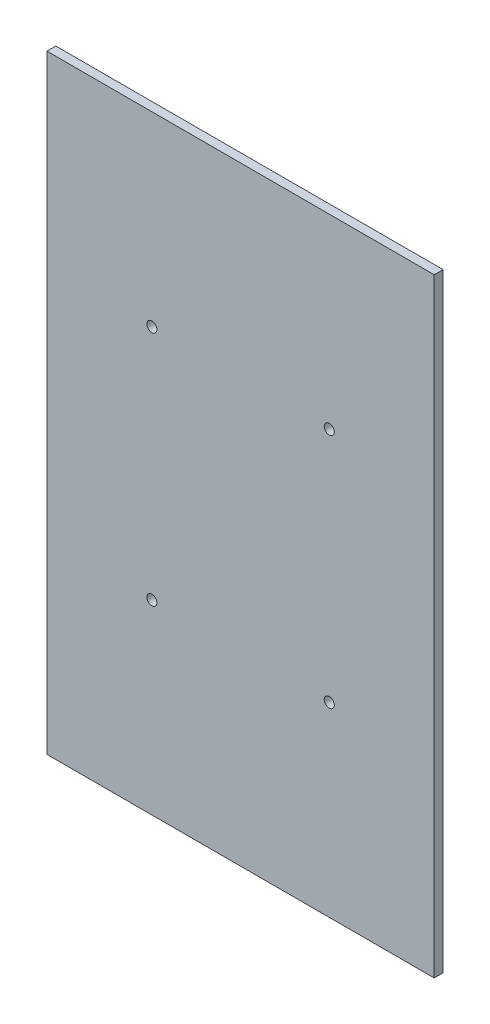
SolidWorks part; units mm, degrees
ref_plane "Front Plane" through (0, 0, 0) normal (0, 0, 1) x (1, 0, 0)
ref_plane "Top Plane" through (0, 0, 0) normal (0, 1, 0) x (1, 0, 0)
ref_plane "Right Plane" through (0, 0, 0) normal (1, 0, 0) x (0, 0, -1)
sketch "Sketch2" plane through (0, 0, 0) normal (0, 0, 1) x (1, 0, 0)
  line L1 (-65.5, -103) -> (65.5, -103)
  line L2 (-65.5, -103) -> (-65.5, 103)
  line L3 (-65.5, 103) -> (65.5, 103)
  line L4 (65.5, -103) -> (65.5, 103)
  line L5 (-65.5, -103) -> (65.5, 103) construction
  line L6 (-65.5, 103) -> (65.5, -103) construction
  point P0 (0, 0)
  dimension "D1" = 131
  dimension "D2" = 206
extrude "Boss-Extrude1" add sketch "Sketch2" along normal blind 3
sketch "Sketch3" plane through (0, 0, 0) normal (0, 0, -1) x (-1, 0, 0)
  line L0 (0, 0) -> (0, -45) construction
  line L1 (-35, -45) -> (35, -45) construction
  line L2 (-35, -45) -> (-35, 45) construction
  line L3 (-35, 45) -> (35, 45) construction
  line L4 (35, -45) -> (35, 45) construction
  line L5 (-35, -45) -> (35, 45) construction
  line L6 (-35, 45) -> (35, -45) construction
  line L7 (0, 0) -> (35, 0) construction
  circle A0 centre (-30, 40) radius 1.7
  circle A1 centre (-30, -40) radius 1.7
  circle A2 centre (30, -40) radius 1.7
  circle A3 centre (30, 40) radius 1.7
  point P0 (0, 0)
  dimension "D3" = 3.4
  dimension "D4" = 5
  dimension "D5" = 5
  dimension "D1" = 70
  dimension "D2" = 90
extrude "Cut-Extrude1" cut sketch "Sketch3" against normal blind 3
